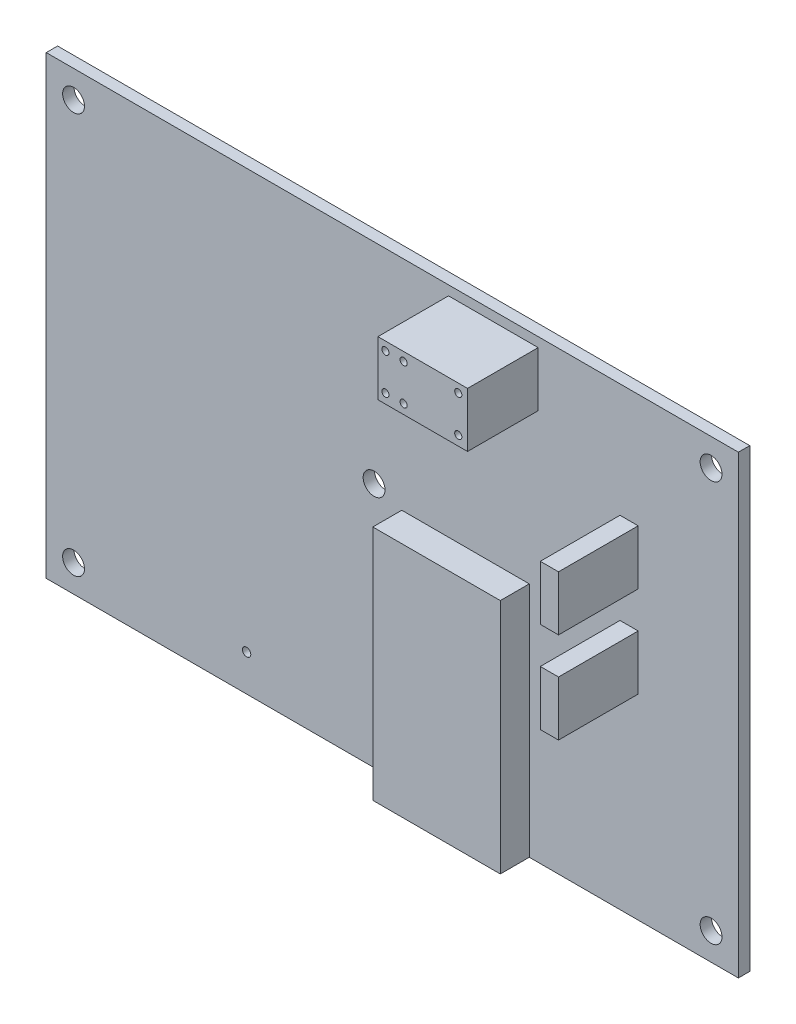
SolidWorks part; units mm, degrees
ref_plane "Front Plane" through (0, 0, 0) normal (0, 0, 1) x (1, 0, 0)
ref_plane "Top Plane" through (0, 0, 0) normal (0, 1, 0) x (1, 0, 0)
ref_plane "Right Plane" through (0, 0, 0) normal (1, 0, 0) x (0, 0, -1)
sketch "Sketch1" plane through (0, 0, 0) normal (0, 0, 1) x (1, 0, 0)
  line L1 (-96.52, 63.5) -> (0, 63.5)
  line L2 (-96.52, 63.5) -> (-96.52, 0)
  line L3 (-96.52, 0) -> (0, 0)
  line L4 (0, 63.5) -> (0, 0)
  dimension "D1" = 63.5
  dimension "D2" = 96.52
extrude "Boss-Extrude1" add sketch "Sketch1" along normal blind 1.5875
sketch "Sketch2" plane through (0, 0, 1.5875) normal (0, 0, 1) x (1, 0, 0)
  line L0 (-96.52, 63.5) -> (-96.52, 0) construction
  line L2 (-96.52, 0) -> (0, 0) construction
  circle A0 centre (-68.58, 5.08) radius 0.5842
  circle A1 centre (-50.8, 34.29) radius 1.524
  circle A2 centre (-15.24, 46.355) radius 0.508
  circle A3 centre (-15.24, 43.815) radius 0.508
  circle A4 centre (-15.24, 41.275) radius 0.508
  circle A5 centre (-15.24, 33.655) radius 0.508
  circle A6 centre (-15.24, 31.115) radius 0.508
  circle A7 centre (-15.24, 28.575) radius 0.508
  point P20 (0, 0)
  point P21 (0, 0)
  dimension "D1" = 1.1684
  dimension "D4" = 3.048
  dimension "D7" = 2.54
  dimension "D11" = 1.016
  dimension "D2" = 27.94
  dimension "D3" = 5.08
  dimension "D5" = 45.72
  dimension "D6" = 34.29
  dimension "D8" = 2.54
  dimension "D9" = 2.54
  dimension "D10" = 2.54
  dimension "D12" = 81.28
  dimension "D13" = 46.355
  dimension "D14" = 33.655
extrude "Holes" cut sketch "Sketch2" against normal through all
sketch "Sketch3" plane through (0, 0, 1.5875) normal (0, 0, 1) x (1, 0, 0)
  line L0 (-96.52, 0) -> (0, 0) construction
  line L1 (-46.9392, 33.02) -> (-29.1592, 33.02)
  line L2 (-46.9392, 33.02) -> (-46.9392, 0)
  line L3 (-46.9392, 0) -> (-29.1592, 0)
  line L4 (-29.1592, 33.02) -> (-29.1592, 0)
  line L5 (-96.52, 63.5) -> (-96.52, 0) construction
  dimension "D1" = 49.5808
  dimension "D2" = 17.78
  dimension "D3" = 33.02
extrude "pro micro" add sketch "Sketch3" along normal blind 4.0386
sketch "Sketch4" plane through (0, 0, 1.5875) normal (0, 0, 1) x (1, 0, 0)
  line L0 (-96.52, 63.5) -> (-96.52, 0) construction
  line L1 (-96.52, 0) -> (-46.9392, 0) construction
  line L2 (0, 63.5) -> (-96.52, 63.5) construction
  line L3 (0, 0) -> (0, 63.5) construction
  circle A0 centre (-92.71, 3.81) radius 1.524
  circle A1 centre (-92.71, 59.69) radius 1.524
  circle A2 centre (-3.81, 59.69) radius 1.524
  circle A3 centre (-3.81, 3.81) radius 1.524
  dimension "D1" = 3.048
  dimension "D2" = 3.81
  dimension "D3" = 3.81
  dimension "D4" = 3.81
  dimension "D5" = 3.81
extrude "mounting holes" cut sketch "Sketch4" against normal through all
sketch "Sketch5" plane through (0, 0, 1.5875) normal (0, 0, 1) x (1, 0, 0)
  line L0 (-96.52, 63.5) -> (-96.52, 0) construction
  line L1 (-40.42, 62.17) -> (-27.92, 62.17)
  line L2 (-40.42, 62.17) -> (-40.42, 54.55)
  line L3 (-40.42, 54.55) -> (-27.92, 54.55)
  line L4 (-27.92, 62.17) -> (-27.92, 54.55)
  line L5 (-96.52, 0) -> (-46.9392, 0) construction
  circle A0 centre (-39.37, 60.96) radius 0.5
  circle A1 centre (-39.37, 55.88) radius 0.5
  circle A2 centre (-36.83, 60.96) radius 0.5
  circle A3 centre (-29.21, 60.96) radius 0.5
  circle A4 centre (-36.83, 55.88) radius 0.5
  circle A5 centre (-29.21, 55.88) radius 0.5
  dimension "D3" = 1
  dimension "D1" = 7.62
  dimension "D2" = 12.5
  dimension "D4" = 5.08
  dimension "D5" = 7.62
  dimension "D6" = 2.54
  dimension "D7" = 1.05
  dimension "D8" = 1.21
  dimension "D9" = 57.15
  dimension "D10" = 55.88
extrude "DC relay" add sketch "Sketch5" along normal blind 9.85
sketch "Sketch6" plane through (0, 0, 1.5875) normal (0, 0, 1) x (1, 0, 0)
  line L1 (-16.51, 47.625) -> (-13.97, 47.625)
  line L2 (-16.51, 47.625) -> (-16.51, 40.005)
  line L3 (-16.51, 40.005) -> (-13.97, 40.005)
  line L4 (-13.97, 47.625) -> (-13.97, 40.005)
  line L5 (-16.51, 34.925) -> (-13.97, 34.925)
  line L6 (-16.51, 34.925) -> (-16.51, 27.305)
  line L7 (-16.51, 27.305) -> (-13.97, 27.305)
  line L8 (-13.97, 34.925) -> (-13.97, 27.305)
  circle A0 centre (-15.24, 43.815) radius 0.508 construction
  circle A1 centre (-15.24, 31.115) radius 0.508 construction
  circle A2 centre (-15.24, 43.815) radius 0.508 construction
  circle A3 centre (-15.24, 31.115) radius 0.508 construction
  point P16 (-15.24, 47.625)
  point P17 (-13.97, 43.815)
  point P18 (-15.24, 34.925)
  point P19 (-13.97, 31.115)
  dimension "D1" = 2.54
  dimension "D2" = 7.62
extrude "Boss-Extrude2" add sketch "Sketch6" along normal blind 11.1125
